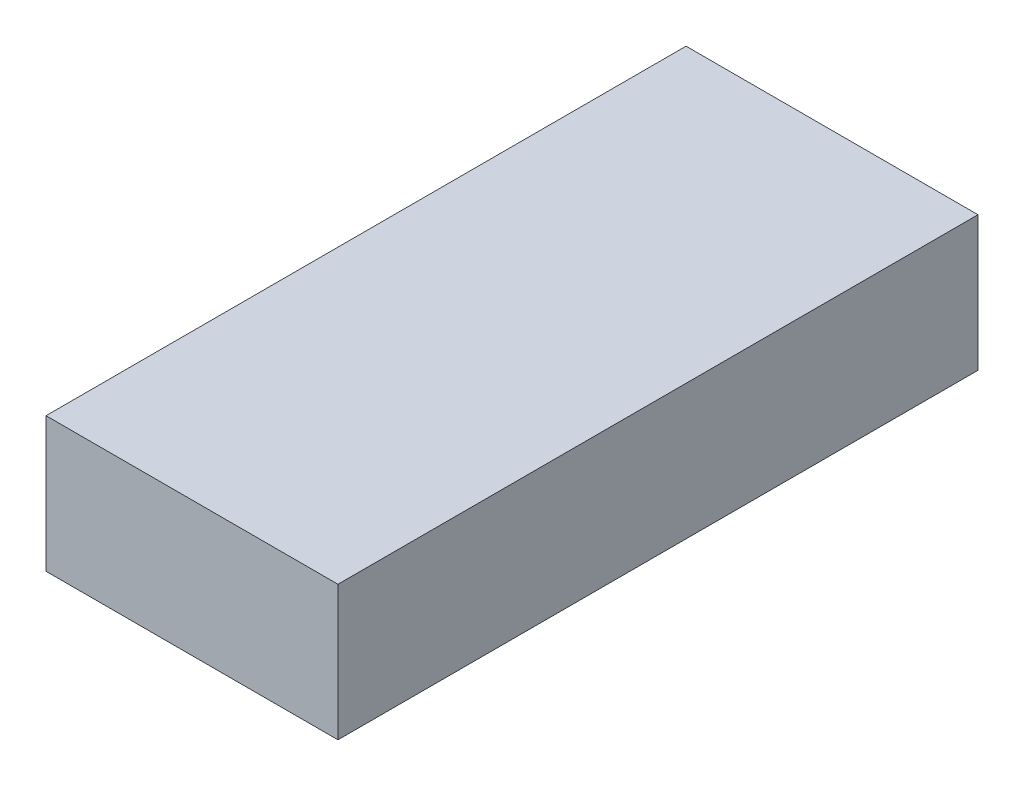
SolidWorks part; units mm, degrees
material "1060 Alloy"
ref_plane "Front" through (0, 0, 0) normal (0, 0, 1) x (1, 0, 0)
ref_plane "Top" through (0, 0, 0) normal (0, 1, 0) x (1, 0, 0)
ref_plane "Right" through (0, 0, 0) normal (1, 0, 0) x (0, 0, -1)
sketch "Sketch1" plane through (0, 0, 0) normal (0, 0, 1) x (1, 0, 0)
  line L1 (0, 0) -> (26, 0)
  line L2 (0, 0) -> (0, 12)
  line L3 (0, 12) -> (26, 12)
  line L4 (26, 0) -> (26, 12)
  dimension "D1" = 26
  dimension "D2" = 12
extrude "Boss-Extrude1" add sketch "Sketch1" along normal blind 57
